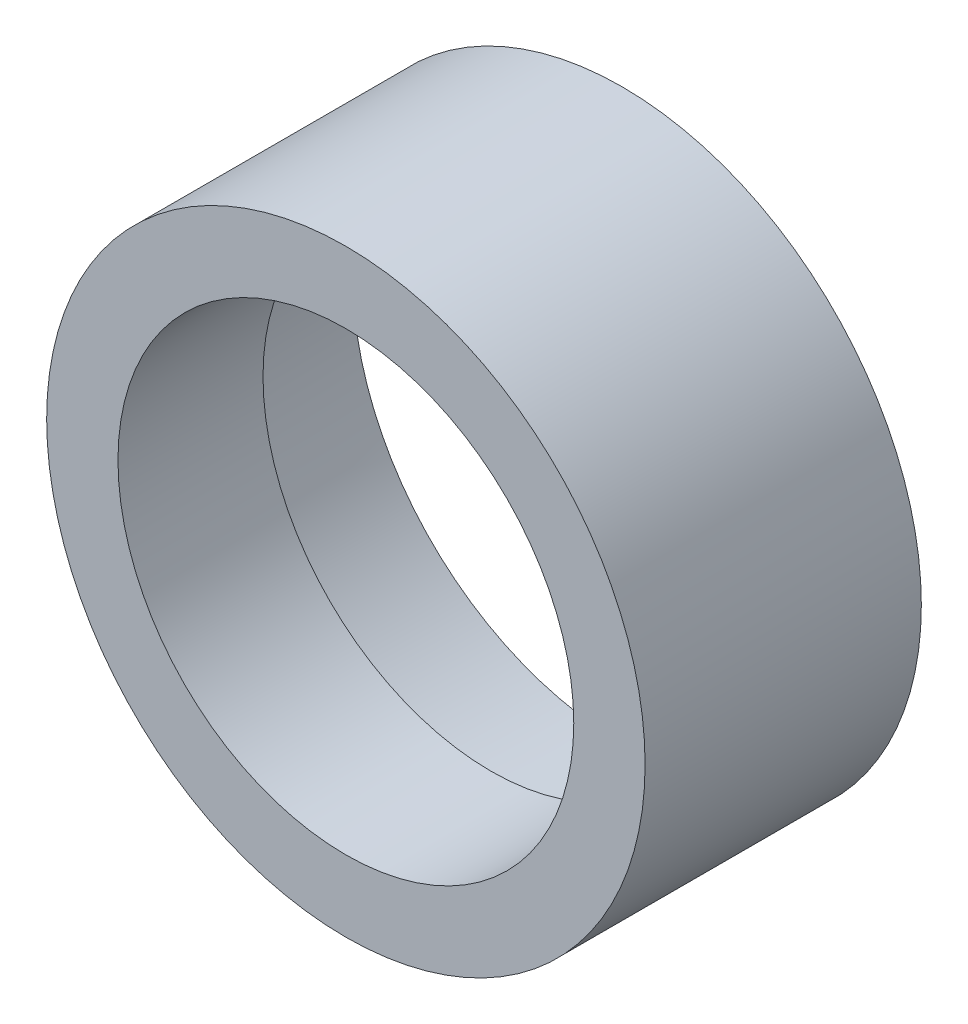
SolidWorks part; units mm, degrees
ref_plane "Front Plane" through (0, 0, 0) normal (1, 0, 0) x (0, 1, 0)
ref_plane "Top Plane" through (0, 0, 0) normal (0, 0, 1) x (0, 1, 0)
ref_plane "Right Plane" through (0, 0, 0) normal (0, 1, 0) x (-1, 0, 0)
sketch "Sketch1" plane through (0, 0, 0) normal (0, 1, 0) x (-1, 0, 0)
  line L0 (19.5, 0) -> (19.25, 8)
  line L1 (19.25, 8) -> (16.5, 9.5)
  line L2 (16.5, 9.5) -> (16.5, 20)
  line L3 (16.5, 20) -> (0, 20) construction
  line L4 (0, 20) -> (0, 0) construction
  line L5 (0, 0) -> (19.5, 0) construction
  line L6 (16.5, 20) -> (21.6633, 20)
  line L7 (21.6633, 20) -> (21.6633, 0)
  line L8 (21.6633, 0) -> (19.5, 0)
  dimension "D1" = 19.5
  dimension "D2" = 8
  dimension "D3" = 19.25
  dimension "D4" = 16.5
  dimension "D5" = 9.5
  dimension "D6" = 20
  dimension "D7" = 16.5
revolve "Revolve1" add sketch "Sketch1" angle 360 about L4
